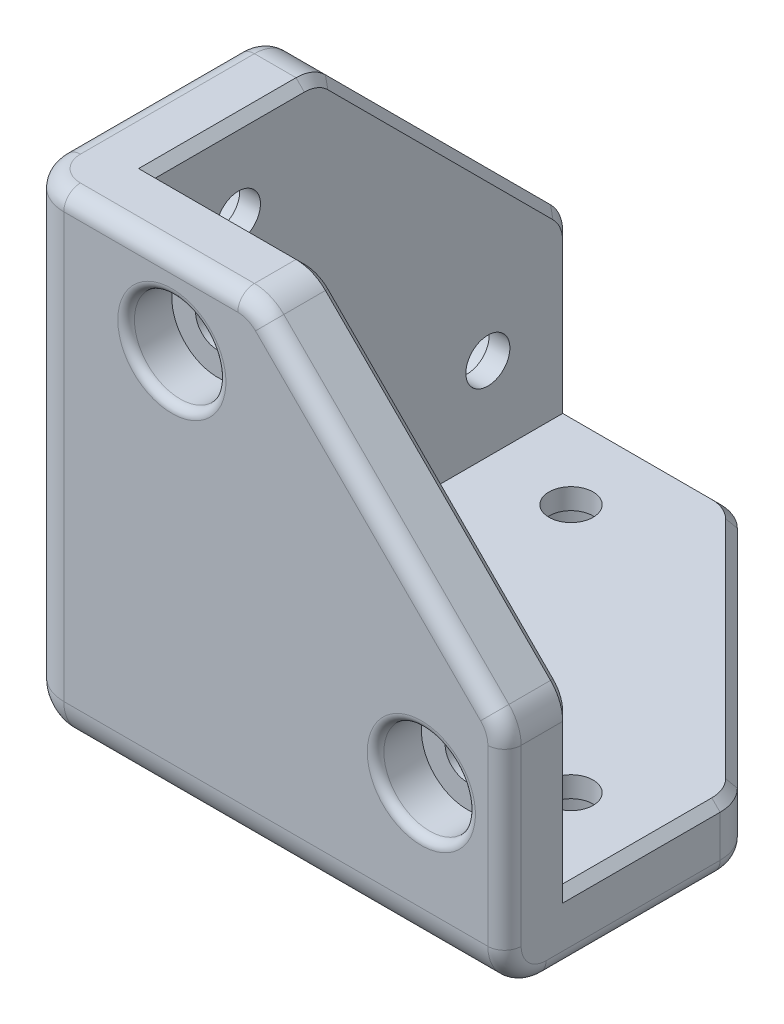
SolidWorks part; units mm, degrees
ref_plane "Front Plane" through (0, 0, 0) normal (0, 0, 1) x (1, 0, 0)
ref_plane "Top Plane" through (0, 0, 0) normal (0, 1, 0) x (1, 0, 0)
ref_plane "Right Plane" through (0, 0, 0) normal (1, 0, 0) x (0, 0, -1)
sketch "Sketch1" plane through (0, 0, 0) normal (0, 1, 0) x (1, 0, 0)
  line L3 (29, -29) -> (-29, -29)
  line L4 (-29, 29) -> (-29, -29)
  line L5 (29, 29) -> (-29, -29) construction
  line L6 (29, -29) -> (-29, 29) construction
  line L9 (-29, 29) -> (29, 29)
  line L10 (29, 29) -> (29, -29)
  point P0 (0, 0)
  dimension "D1" = 58
  dimension "D2" = 58
extrude "Boss-Extrude1" add sketch "Sketch1" along normal blind 58
sketch "Sketch2" plane through (0, 0, 29) normal (0, 0, 1) x (1, 0, 0)
  line L0 (-29, 0) -> (-29, 33.6747)
  line L1 (-29, 33.6747) -> (-11.0526, 33.6747)
  dimension "D1" = 33.6747
sketch "Sketch3" plane through (0, 58, 0) normal (0, 1, 0) x (1, 0, 0)
  line L0 (-29, 29) -> (-21, 29)
  line L1 (29, 29) -> (-29, 29) construction
  line L2 (-21, 29) -> (-21, -21)
  line L3 (-21, -21) -> (29, -21)
  line L4 (29, -29) -> (29, 29) construction
  line L5 (29, -21) -> (29, 29)
  line L6 (29, 29) -> (-21, 29)
  line L7 (-29, -29) -> (29, -29) construction
  line M5 (29, -29) -> (29, 29)
  line M6 (29, 29) -> (-29, 29)
  dimension "D1" = 8
  dimension "D2" = 8
extrude "Cut-Extrude1" cut sketch "Sketch3" against normal blind 50 contours L2 L3 M5 M6
sketch "Sketch4" plane through (0, 0, 21) normal (0, 0, -1) x (-1, 0, 0)
  line L1 (-29, 8) -> (-29, 58) construction
  line L2 (-29, 28) -> (1, 58)
  line L3 (21, 58) -> (-29, 58) construction
  line L5 (-29, 28) -> (-29, 58)
  line L6 (-29, 58) -> (1, 58)
extrude "Cut-Extrude2" cut sketch "Sketch4" against normal blind 8
sketch "Sketch5" plane through (-21, 0, 0) normal (1, 0, 0) x (0, 0, -1)
  line L0 (-1, 58) -> (29, 28)
  line L1 (29, 58) -> (-21, 58) construction
  line L2 (29, 8) -> (29, 58) construction
  line L3 (-1, 58) -> (29, 58)
  line L4 (29, 58) -> (29, 28)
  dimension "D1" = 20
  dimension "D2" = 20
extrude "Cut-Extrude3" cut sketch "Sketch5" against normal blind 8
sketch "Sketch6" plane through (0, 8, 0) normal (0, 1, 0) x (1, 0, 0)
  line L0 (-1, 29) -> (29, -1)
  line L1 (29, 29) -> (-21, 29) construction
  line L2 (29, -21) -> (29, 29) construction
  line L3 (-1, 29) -> (29, 29)
  line L4 (29, 29) -> (29, -1)
  dimension "D1" = 20
  dimension "D2" = 20
extrude "Cut-Extrude4" cut sketch "Sketch6" against normal blind 8
fillet "Fillet1" radius 5 9 edges at (-29, 0, 0) (0, 0, 29) (-29, 29, 29) (29, 4, 1) (-25, 58, 1) (-25, 28, -29) (-1, 58, 25) (29, 28, 25) (-1, 4, -29)
sketch "Sketch7" plane through (0, 8, 0) normal (0, 1, 0) x (1, 0, 0)
  line L1 (-21, -21) -> (-1, -21)
  line L2 (-21, -21) -> (-21, -1)
  line L3 (-21, -1) -> (-1, -1)
  line L4 (-1, -21) -> (-1, -1)
  dimension "D1" = 20
  dimension "D2" = 20
sketch "Sketch8" plane through (-29, 0, 0) normal (-1, 0, 0) x (0, 0, 1)
  line L1 (21, 8) -> (1, 8)
  line L2 (21, 8) -> (21, 28)
  line L3 (21, 28) -> (1, 28)
  line L4 (1, 8) -> (1, 28)
  dimension "D1" = 20
sketch "Sketch9" plane through (0, 0, 21) normal (0, 0, -1) x (-1, 0, 0)
  line L1 (21, 8) -> (1, 8)
  line L2 (21, 8) -> (21, 28)
  line L3 (21, 28) -> (1, 28)
  line L4 (1, 8) -> (1, 28)
  dimension "D1" = 20
  dimension "D2" = 20
sketch "Sketch10" plane through (0, 0, 29) normal (0, 0, 1) x (1, 0, 0)
  line L0 (-21, 8) -> (29, 8) construction
  line L1 (29, 8) -> (29, 25.9289) construction
  line L2 (14, 43) -> (-24, 5) construction
  line L3 (27.5355, 29.4645) -> (0.4645, 56.5355) construction
  circle A0 centre (19, 18) radius 2.65
  circle A2 centre (-11, 48) radius 2.65
  dimension "D2" = 5.3
  dimension "D1" = 10
  dimension "D3" = 10
extrude "Cut-Extrude5" cut sketch "Sketch10" against normal blind 8
sketch "Sketch11" plane through (-29, 0, 0) normal (-1, 0, 0) x (0, 0, 1)
  line L0 (-29, 25.9289) -> (-29, 5) construction
  line L1 (-14, 43) -> (24, 5) construction
  line L2 (-0.4645, 56.5355) -> (-27.5355, 29.4645) construction
  circle A0 centre (-19, 18) radius 2.65
  circle A2 centre (11, 48) radius 2.65
  dimension "D1" = 5.3
  dimension "D2" = 10
extrude "Cut-Extrude6" cut sketch "Sketch11" against normal blind 8
sketch "Sketch12" plane through (0, 0, 0) normal (0, -1, 0) x (1, 0, 0)
  line L0 (-3.0711, -29) -> (-24, -29) construction
  line L1 (29, 24) -> (29, 3.0711) construction
  circle A0 centre (-11, -19) radius 2.65
  circle A2 centre (19, 11) radius 2.65
  dimension "D1" = 5.3
  dimension "D4" = 5.3
  dimension "D2" = 10
  dimension "D5" = 10
extrude "Cut-Extrude7" cut sketch "Sketch12" against normal blind 8
ref_plane "Plane1" through (0, 5.5, 0) normal (0, 1, 0) x (1, 0, 0)
sketch "Sketch13" plane through (0, 5.5, 0) normal (0, 1, 0) x (1, 0, 0)
  circle A0 centre (-11, 19) radius 5.5
  circle A1 centre (19, -11) radius 5.5
  dimension "D1" = 11
  dimension "D2" = 11
extrude "Cut-Extrude8" cut sketch "Sketch13" against normal blind 5.5
sketch "Sketch14" plane through (-29, 0, 0) normal (-1, 0, 0) x (0, 0, 1)
  circle A0 centre (-19, 18) radius 5.5
  circle A1 centre (11, 48) radius 5.5
  dimension "D1" = 11
  dimension "D2" = 11
extrude "Cut-Extrude9" cut sketch "Sketch14" against normal blind 5.5
sketch "Sketch15" plane through (0, 0, 29) normal (0, 0, 1) x (1, 0, 0)
  circle A0 centre (-11, 48) radius 5.5
  circle A1 centre (19, 18) radius 5.5
  dimension "D1" = 11
  dimension "D2" = 11
extrude "Cut-Extrude10" cut sketch "Sketch15" against normal blind 5.5
fillet "Fillet2" radius 1 6 edges at (-29, 48, 16.5) (-29, 18, -13.5) (-11, 0, -13.5) (19, 0, 16.5) (24.5, 18, 29) (-5.5, 48, 29)
fillet "Fillet3" radius 2 18 edges at (-1.1577, 0, -28.6194) (-13.5355, 0, -29) (-27.5355, 1.4645, -29) (-29, 15.4645, -29) (-29, 27.8423, -28.6194) (-29, 43, -14) (-29, 57.6194, 1.1577) (-29, 58, 13.5355) (-27.5355, 58, 27.5355) (-13.5355, 58, 29) (-1.1577, 57.6194, 29) (14, 43, 29) (28.6194, 27.8423, 29) (29, 15.4645, 29) (29, 1.4645, 27.5355) (29, 0, 13.5355) (28.6194, 0, 1.1577) (14, 0, -14)
chamfer "Chamfer1" distance 1 angle 45 15 edges at (-21, 16.9645, -29) (-21, 27.8423, -28.6194) (-21, 43, -14) (-21, 57.6194, 1.1577) (-21, 58, 12.0355) (-12.0355, 58, 21) (-1.1577, 57.6194, 21) (14, 43, 21) (28.6194, 27.8423, 21) (29, 16.9645, 21) (-12.0355, 8, -29) (29, 8, 12.0355) (-1.1577, 8, -28.6194) (28.6194, 8, 1.1577) (14, 8, -14)
